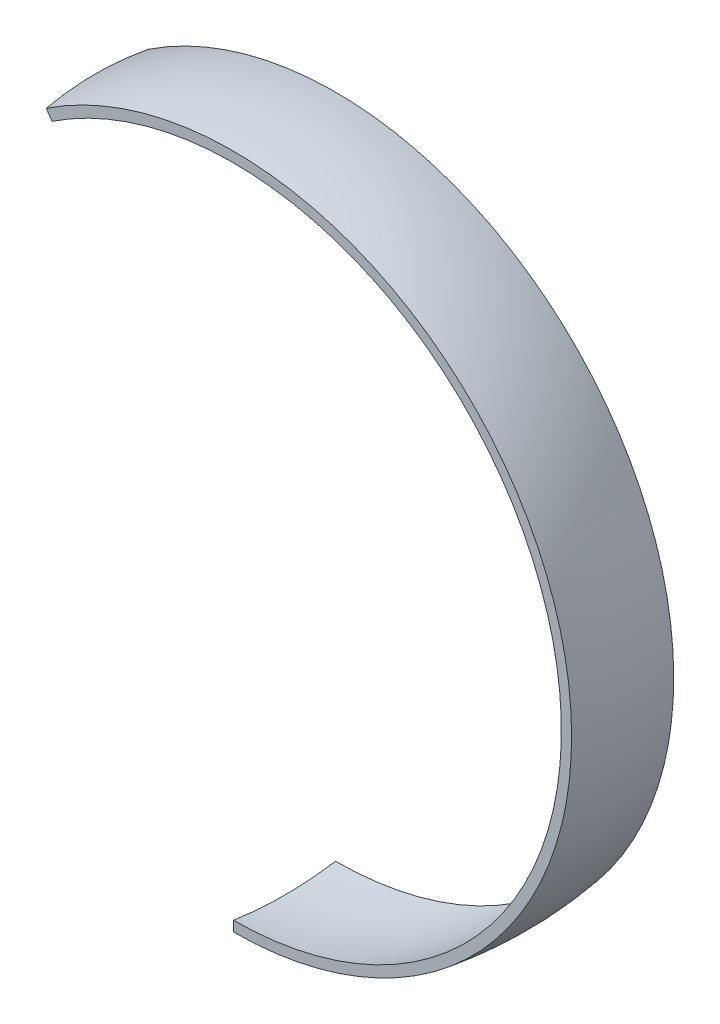
SolidWorks part; units mm, degrees
ref_plane "Front Plane" through (0, 0, 0) normal (0, 0, 1) x (1, 0, 0)
ref_plane "Top Plane" through (0, 0, 0) normal (0, 1, 0) x (1, 0, 0)
ref_plane "Right Plane" through (0, 0, 0) normal (1, 0, 0) x (0, 0, -1)
sketch "Sketch1" plane through (0, 0, 0) normal (1, 0, 0) x (0, 0, -1)
  line L0 (-25.4, -168.2145) -> (-25.4, -163.1345)
  line L1 (25.4, -168.2145) -> (25.4, -163.1345)
  arc A0 (-25.4, -168.2145) -> (25.4, -168.2145) centre (0, 0) ccw
  arc A1 (-25.4, -163.1345) -> (25.4, -163.1345) centre (0, 0) ccw
  point P4 (0, -170.1213)
  dimension "D1" = 165.1
  dimension "D3" = 50.8
  dimension "D2" = 5.08
sketch "Sketch2" plane through (0, 0, 0) normal (0, 0, 1) x (1, 0, 0)
  line L0 (0, 0) -> (-90.8211, 136.6967) construction
  line L1 (0, 0) -> (0, -164.1172) construction
  line L5 (0, -165.1) -> (0, -163.1345) construction
  arc A0 (0, -164.1172) -> (-90.8211, 136.6967) centre (0, 0) ccw
  point P2 (0, -163.5592)
  point P5 (-162.5568, -18.0801)
  point P10 (0, -164.1172)
  dimension "D1" = 213.6
sweep "Sweep2" add profiles "Sketch1" path "Sketch2"
